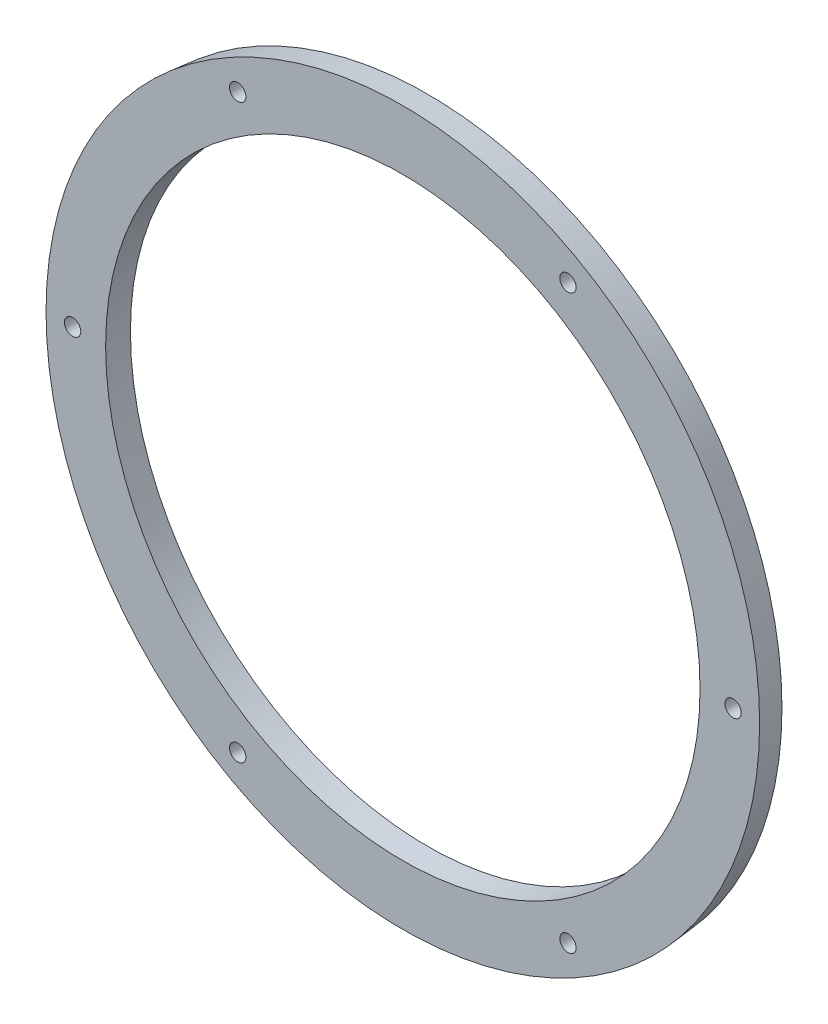
SolidWorks part; units mm, degrees
material "Balsa"
ref_plane "Ebene vorne" through (0, 0, 0) normal (0, 0, 1) x (1, 0, 0)
ref_plane "Ebene oben" through (0, 0, 0) normal (0, 1, 0) x (1, 0, 0)
ref_plane "Ebene rechts" through (0, 0, 0) normal (1, 0, 0) x (0, 0, -1)
sketch "Sketch1" plane through (0, 0, 0) normal (0, 0, 1) x (1, 0, 0)
  line L0 (0, 0) -> (66.5, 0) construction
  circle A0 centre (0, 0) radius 71.85
  circle A1 centre (0, 0) radius 59.85
  circle A2 centre (66.5, 0) radius 1.65
  circle A3 centre (33.25, -57.5907) radius 1.65
  circle A4 centre (-33.25, -57.5907) radius 1.65
  circle A5 centre (-66.5, 0) radius 1.65
  circle A6 centre (-33.25, 57.5907) radius 1.65
  circle A7 centre (33.25, 57.5907) radius 1.65
  point P18 (0, 0)
  dimension "D1" = 143.7
  dimension "D2" = 12
  dimension "D4" = 3.3
  dimension "D3" = 66.5
  dimension "D5" = 6
extrude "Boss-Extrude1" add sketch "Sketch1" along normal blind 5
sketch "Sketch2" plane through (0, 0, 0) normal (0, 1, 0) x (1, 0, 0)
  line L0 (0, 0) -> (71.35, 0) construction
  line L1 (71.35, 0) -> (71.85, 0)
  line L2 (71.85, 0) -> (71.85, -5)
  line L3 (71.85, -5) -> (71.35, 0)
  point P3 (69.2883, 0)
  dimension "D1" = 71.85
  dimension "D2" = 0.5
  dimension "D3" = 5
ref_axis "Axis1" through (0, 0, 0) along (0, 0, 1)
revolve "Cut-Revolve1" cut sketch "Sketch2" angle 360 about axis through (0, 0, 0) along (0, 0, 1)
equation "\"D1@Sketch2\"=143.7/2"
